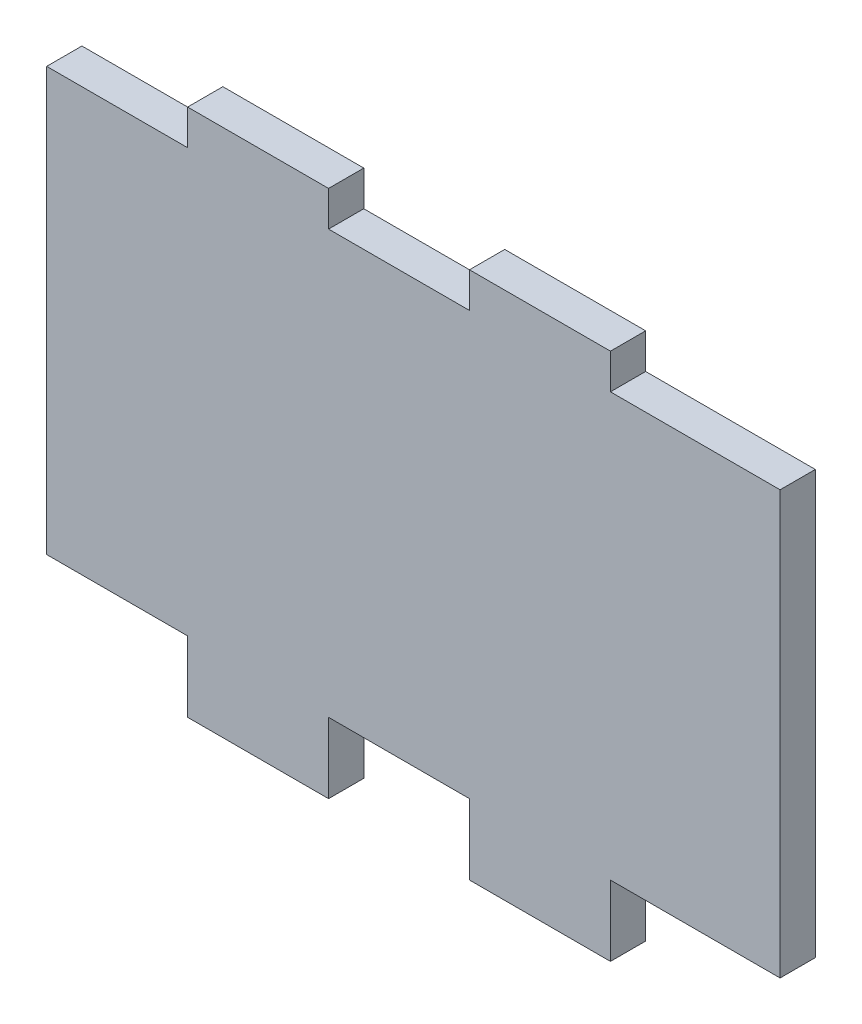
SolidWorks part; units mm, degrees
material "Beech"
ref_plane "Front" through (0, 0, 0) normal (0, 0, 1) x (1, 0, 0)
ref_plane "Top" through (0, 0, 0) normal (0, 1, 0) x (1, 0, 0)
ref_plane "Right" through (0, 0, 0) normal (1, 0, 0) x (0, 0, -1)
sketch "Sketch1" plane through (0, 0, 0) normal (0, 0, 1) x (1, 0, 0)
  line L1 (-26.0188, -18.75) -> (26.0188, -18.75) construction
  line L2 (-26.0188, -18.75) -> (-26.0188, 18.75) construction
  line L3 (-26.0188, 18.75) -> (26.0188, 18.75) construction
  line L4 (26.0188, -18.75) -> (26.0188, 18.75) construction
  line L5 (-26.0188, -18.75) -> (26.0188, 18.75) construction
  line L6 (-26.0188, 18.75) -> (26.0188, -18.75) construction
  line L7 (-26.0188, 16.25) -> (-16.0188, 16.25)
  line L8 (-16.0188, 16.25) -> (-16.0188, 18.75)
  line L9 (-16.0188, 18.75) -> (-6.0188, 18.75)
  line L10 (-6.0188, 18.75) -> (-6.0188, 16.25)
  line L11 (-6.0188, 16.25) -> (3.9812, 16.25)
  line L12 (3.9812, 16.25) -> (3.9812, 18.75)
  line L13 (3.9812, 18.75) -> (13.9812, 18.75)
  line L14 (13.9812, 18.75) -> (13.9812, 16.25)
  line L15 (13.9812, 16.25) -> (26.0188, 16.25)
  line L17 (-6.0188, 0) -> (5.1467, 0) construction
  line L19 (13.9812, -18.75) -> (13.9812, -13.75)
  line L20 (3.9812, -18.75) -> (13.9812, -18.75)
  line L21 (3.9812, -13.75) -> (3.9812, -18.75)
  line L22 (-6.0188, -13.75) -> (3.9812, -13.75)
  line L23 (-6.0188, -18.75) -> (-6.0188, -13.75)
  line L24 (-16.0188, -18.75) -> (-6.0188, -18.75)
  line L25 (-16.0188, -13.75) -> (-16.0188, -18.75)
  line L26 (-26.0188, -13.75) -> (-16.0188, -13.75)
  line L27 (13.9812, -13.75) -> (26.0188, -13.75)
  line L28 (-26.0188, 16.25) -> (-26.0188, -13.75)
  line L29 (26.0188, 16.25) -> (26.0188, -13.75)
  point P0 (0, 0)
  point P6 (0, 0)
  point P21 (26.0188, 0)
  point P30 (-26.0188, 0)
  dimension "D1" = 52.0377
  dimension "D2" = 37.5
  dimension "D3" = 5
  dimension "D4" = 10
  dimension "D5" = 10
extrude "Boss-Extrude1" add sketch "Sketch1" along normal blind 2.5
